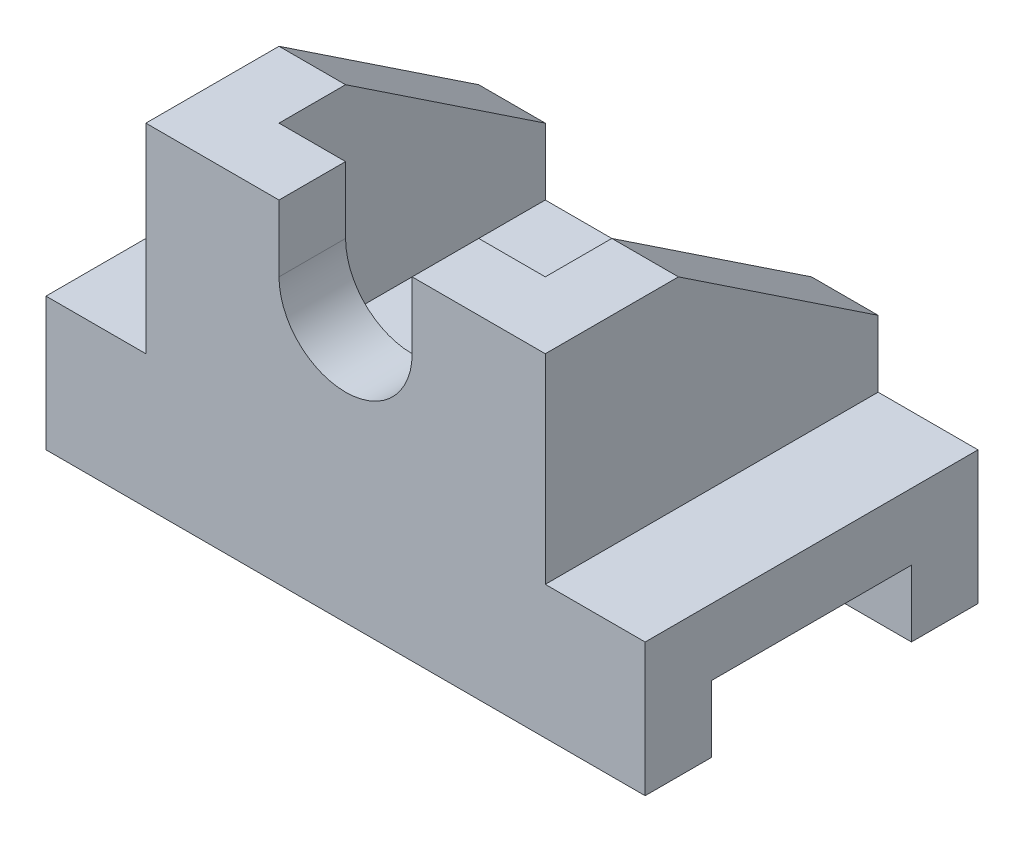
SolidWorks part; units mm, degrees
other "Camera1"
ref_plane "Front Plane" through (0, 0, 0) normal (0, 0, 1) x (1, 0, 0)
ref_plane "Top Plane" through (0, 0, 0) normal (0, 1, 0) x (1, 0, 0)
ref_plane "Right Plane" through (0, 0, 0) normal (1, 0, 0) x (0, 0, -1)
sketch "Sketch2" plane through (0, 0, 0) normal (0, 1, 0) x (1, 0, 0)
  line L1 (-90, 50) -> (90, 50)
  line L2 (-90, 50) -> (-90, -50)
  line L3 (-90, -50) -> (90, -50)
  line L4 (90, 50) -> (90, -50)
  line L5 (-90, 50) -> (90, -50) construction
  line L6 (-90, -50) -> (90, 50) construction
  point P0 (0, 0)
  dimension "D1" = 100
  dimension "D2" = 180
extrude "Boss-Extrude2" add sketch "Sketch2" against normal blind 40
sketch "Sketch6" plane through (0, 0, 0) normal (1, 0, 0) x (0, 0, -1)
  line L0 (50, 0) -> (50, 20)
  line L1 (50, 20) -> (-10, 60)
  line L2 (-10, 60) -> (-50, 60)
  line L3 (-50, 60) -> (-50, 0)
  line L4 (-50, 0) -> (50, 0)
  dimension "D1" = 40
  dimension "D2" = 20
  dimension "D3" = 60
extrude "Boss-Extrude3" add sketch "Sketch6" along normal mid plane 120
sketch "Sketch7" plane through (90, 0, 0) normal (1, 0, 0) x (0, 0, -1)
  line L0 (-50, -40) -> (50, -40) construction
  line L1 (-30, -60) -> (30, -60)
  line L2 (-30, -60) -> (-30, -20)
  line L3 (-30, -20) -> (30, -20)
  line L4 (30, -60) -> (30, -20)
  line L5 (-30, -60) -> (30, -20) construction
  line L6 (-30, -20) -> (30, -60) construction
  point P0 (0, -40)
  point P7 (30, -40)
  dimension "D1" = 60
  dimension "D2" = 20
extrude "Cut-Extrude1" cut sketch "Sketch7" against normal through all
sketch "Sketch15" plane through (0, 0, -50) normal (0, 0, -1) x (-1, 0, 0)
  line L1 (-40, 0) -> (40, 0)
  line L2 (-40, 0) -> (-40, 60)
  line L3 (-40, 60) -> (40, 60)
  line L4 (40, 0) -> (40, 60)
  point P4 (0, 0)
  dimension "D1" = 80
  dimension "D2" = 60
extrude "Cut-Extrude2" cut sketch "Sketch15" against normal blind 80
sketch "Sketch16" plane through (0, 0, 30) normal (0, 0, -1) x (-1, 0, 0)
  line L0 (40, 60) -> (-40, 60) construction
  line L1 (-20, 80) -> (20, 80)
  line L2 (-20, 80) -> (-20, 40)
  line L3 (-20, 40) -> (20, 40)
  line L4 (20, 80) -> (20, 40)
  line L5 (-20, 80) -> (20, 40) construction
  line L6 (-20, 40) -> (20, 80) construction
  circle A0 centre (0, 40) radius 20
  point P0 (0, 60)
  point P9 (-20, 60)
  line M4 (40, 60) -> (-40, 60)
  dimension "D1" = 20
  dimension "D2" = 40
extrude "Cut-Extrude3" cut sketch "Sketch16" against normal blind 20 contours L4 L1 L2 M4 | A0 L2 M4 | L3 A0 | L3 A0 | A0 L4 M4
sketch "Sketch20" plane through (0, 0, 0) normal (0, 1, 0) x (1, 0, 0)
  line L0 (40, 50) -> (-40, 50) construction
  line L1 (40, 50) -> (40, -10) construction
  circle A0 centre (0, 10) radius 20
  dimension "D1" = 40
  dimension "D3" = 40
  dimension "D2" = 40
extrude "Cut-Extrude5" cut sketch "Sketch20" against normal blind 20
